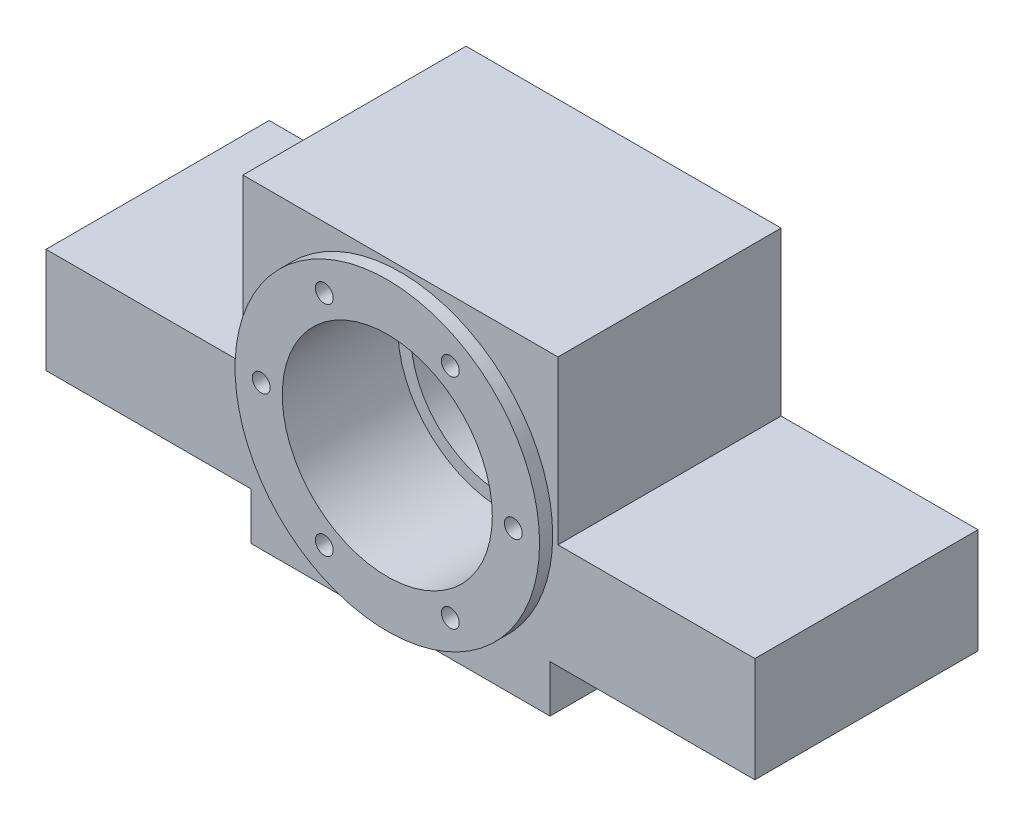
SolidWorks part; units mm, degrees
ref_plane "前视基准面" through (0, 0, 0) normal (0, 0, 1) x (1, 0, 0)
ref_plane "上视基准面" through (0, 0, 0) normal (0, 1, 0) x (1, 0, 0)
ref_plane "右视基准面" through (0, 0, 0) normal (1, 0, 0) x (0, 0, -1)
other "Configuration Table"
sketch "草图1" plane through (0, 0, 0) normal (0, 0, 1) x (1, 0, 0)
  line L0 (57, 0) -> (-57, 0) construction
  line L1 (0, 0) -> (-57, 0)
  line L3 (-135, 58) -> (-135, 18)
  line L5 (135, 58) -> (135, 18)
  line L6 (-57, 0) -> (-57, 18)
  line L7 (-57, 18) -> (-135, 18)
  line L8 (0, 0) -> (57, 0)
  line L9 (57, 0) -> (57, 18)
  line L10 (57, 18) -> (135, 18)
  line L11 (-135, 58) -> (-60, 58)
  line L12 (-60, 58) -> (-60, 120)
  line L13 (-60, 120) -> (60, 120)
  line L14 (60, 120) -> (60, 58)
  line L15 (60, 58) -> (135, 58)
  dimension "D1" = 75
  dimension "D2" = 120
  dimension "D3" = 57
  dimension "D4" = 18
  dimension "D5" = 57
  dimension "D6" = 18
  dimension "D7" = 40
  dimension "D8" = 120
extrude "凸台-拉伸1" add sketch "草图1" against normal blind 85
sketch "草图2" plane through (0, 0, 0) normal (0, 0, 1) x (1, 0, 0)
  line L0 (0, 0) -> (0, 60) construction
  circle A0 centre (0, 60) radius 58
  dimension "D1" = 116
extrude "凸台-拉伸2" add sketch "草图2" along normal blind 5
sketch "草图3" plane through (0, 0, 5) normal (0, 0, 1) x (1, 0, 0)
  circle A0 centre (0, 60) radius 40
extrude "切除-拉伸1" cut sketch "草图3" against normal blind 44
sketch "草图4" plane through (0, 0, -39) normal (0, 0, 1) x (1, 0, 0)
  circle A0 centre (0, 60) radius 35
extrude "切除-拉伸2" cut sketch "草图4" against normal through all
sketch "草图5" plane through (0, 0, 5) normal (0, 0, 1) x (1, 0, 0)
  circle A0 centre (0, 60) radius 48 construction
  point P13 (24, 101.5692)
  dimension "D2" = 96
hole_wizard "M8 螺纹孔1" positions "草图6" profile "草图7" tap size "M8" standard "GB"
sketch "草图6" plane through (0, 0, 5) normal (0, 0, 1) x (1, 0, 0)
  point P0 (24, 101.5692)
sketch "草图7" plane through (24, 101.5692, 5) normal (1, 0, 0) x (0, -1, 0)
  line L0 (0, 0) -> (0, 29.8029)
  line L1 (0, 29.8029) -> (3.4, 27.76)
  line L2 (3.4, 27.76) -> (3.4, 0)
  line L5 (3.4, 0) -> (0, 0)
  line L10 (0, 29.8029) -> (-3.4, 27.76) construction
  line L11 (0, -6.35) -> (0, 107.95) construction
  dimension "螺纹孔钻头直径" = 6.8
  dimension "螺纹孔钻头深度" = 27.76
  dimension "导头角度" = 118
cosmetic thread "孔螺纹线1" parameters "D1"=21, "D2"=8
pattern_circular "阵列(圆周)1" count 6 over 360 about axis through (0, 60, 0) along (0, 0, 1) of "M8 螺纹孔1"
